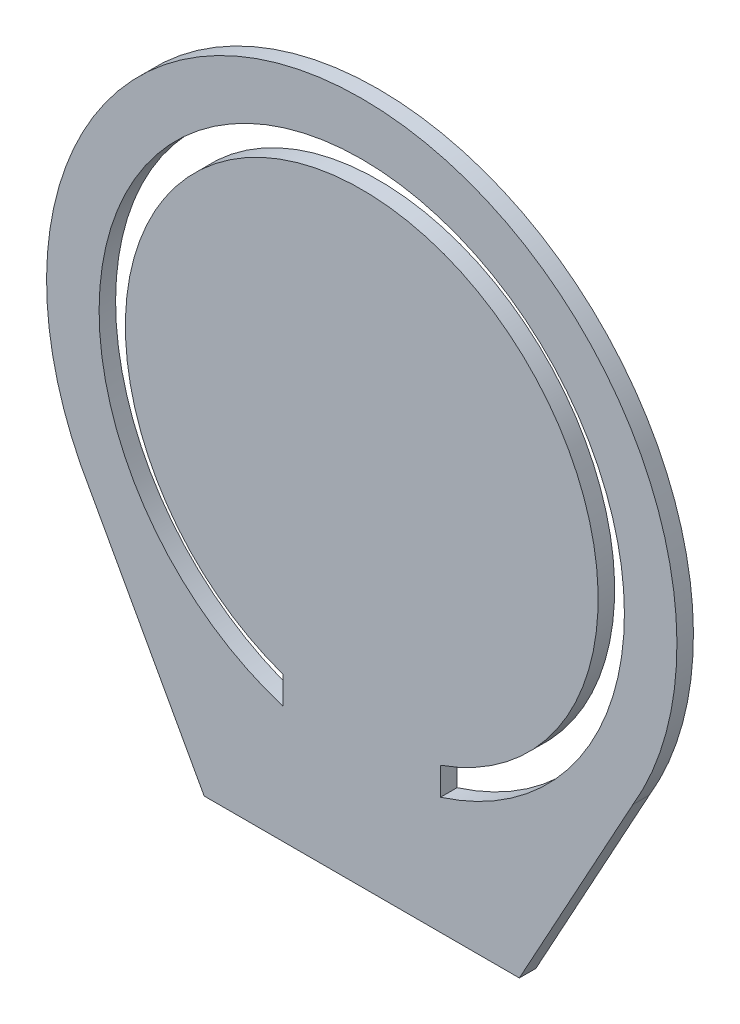
SolidWorks part; units mm, degrees
ref_plane "Plano frontal" through (0, 0, 0) normal (0, 0, 1) x (1, 0, 0)
ref_plane "Plano superior" through (0, 0, 0) normal (0, 1, 0) x (1, 0, 0)
ref_plane "Plano direito" through (0, 0, 0) normal (1, 0, 0) x (0, 0, -1)
other "Bounding Box"
ref_plane "Default Plane" through (30, -35, 0) normal (-1, 0, 0) x (0, 0, 1)
sketch "Esboço1" plane through (0, 0, 0) normal (0, 0, 1) x (1, 0, 0)
  circle A3 centre (0, 0) radius 30
  circle A4 centre (0, 0) radius 25
  dimension "D1" = 60
  dimension "D2" = 50
extrude "Boss-Extrude1" add sketch "Esboço1" along normal blind 1.57
sketch "Sketch1" plane through (0, 0, 1.57) normal (0, 0, 1) x (1, 0, 0)
  line L0 (15, -35) -> (25.8005, -15.3079)
  line L1 (-15, -35) -> (15, -35)
  line L2 (-15, -35) -> (-15, -25)
  line L3 (-15, -25) -> (15, -25)
  line L4 (15, -35) -> (15, -25)
  line L5 (-15, -35) -> (15, -25) construction
  line L6 (-15, -25) -> (15, -35) construction
  line L7 (0, 0) -> (0, -45.5282)
  line L8 (-15, -35) -> (-25.8005, -15.3079)
  line L9 (-25.8005, -15.3079) -> (-15, -25)
  line L10 (15, -25) -> (25.8005, -15.3079)
  circle A0 centre (0, 0) radius 30 construction
  point P2 (0, -30)
  circle M7 centre (0, 0) radius 30
  dimension "D1" = 30
  dimension "D2" = 10
extrude "Boss-Extrude2" add sketch "Sketch1" against normal blind 1.57 contours L8 L2 M7 | L7 L2 L1 M7 | L7 L1 L4 M7 | L4 L0 M7
sketch "Sketch2" plane through (0, 0, 0) normal (0, 0, 1) x (1, 0, 0)
  line L2 (-2.5, -21.2132) -> (2.5, -21.2132)
  line L4 (2.5, -25) -> (-2.5, -25)
  line L5 (2.5, -25) -> (7.5, -25)
  line L6 (7.5, -25) -> (7.5, -21.2132)
  line L7 (7.5, -21.2132) -> (2.5, -21.2132)
  line L9 (-7.5, -25) -> (-7.5, -21.2132)
  line L11 (-2.5, -25) -> (-7.5, -25)
  line L13 (-7.5, -21.2132) -> (-2.5, -21.2132)
  circle A0 centre (0, 0) radius 22.5
  circle A1 centre (0, 0) radius 25 construction
  point P12 (0, -25)
  point P20 (0, -22.3607)
  dimension "D1" = 45
  dimension "D2" = 2.5
  dimension "D3" = 5
extrude "Boss-Extrude3" add sketch "Sketch2" along normal blind 1.57
sketch "Sketch4" plane through (0, 0, 1.57) normal (0, 0, 1) x (1, 0, 0)
  circle A0 centre (0, 0) radius 22.5
  dimension "D1" = 45
extrude "Boss-Extrude4" add sketch "Sketch4" against normal blind 1.57
